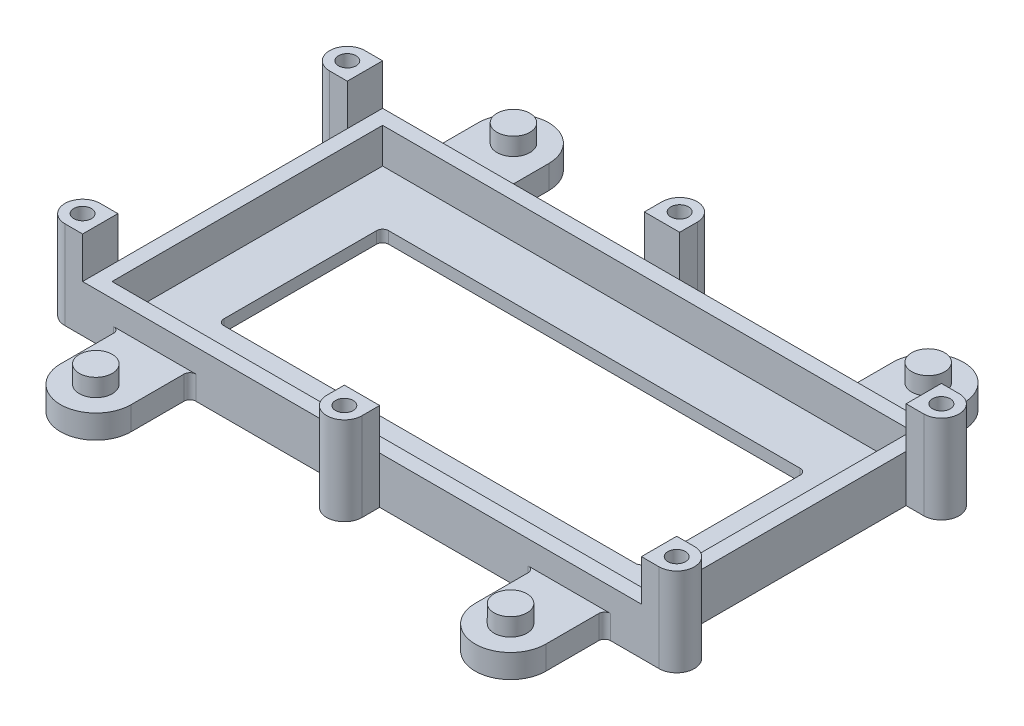
SolidWorks part; units mm, degrees
ref_plane "Front Plane" through (0, 0, 0) normal (0, 0, 1) x (1, 0, 0)
ref_plane "Top Plane" through (0, 0, 0) normal (0, 1, 0) x (1, 0, 0)
ref_plane "Right Plane" through (0, 0, 0) normal (1, 0, 0) x (0, 0, -1)
sketch "Sketch1" plane through (0, 0, 0) normal (0, 1, 0) x (1, 0, 0)
  line L1 (-55.9294, 26.1636) -> (39.0706, 26.1636)
  line L2 (-55.9294, 26.1636) -> (-55.9294, -24.8364)
  line L3 (-55.9294, -24.8364) -> (39.0706, -24.8364)
  line L4 (39.0706, 26.1636) -> (39.0706, -24.8364)
  dimension "D1" = 51
  dimension "D2" = 95
extrude "Boss-Extrude1" add sketch "Sketch1" along normal blind 2
sketch "Sketch2" plane through (0, 2, 0) normal (0, 1, 0) x (1, 0, 0)
  line L1 (-55.9294, 26.1636) -> (39.0706, 26.1636)
  line L2 (-55.9294, 26.1636) -> (-55.9294, -24.8364)
  line L3 (-55.9294, -24.8364) -> (39.0706, -24.8364)
  line L4 (39.0706, 26.1636) -> (39.0706, -24.8364)
  line L5 (36.5706, 23.6636) -> (-53.4294, 23.6636)
  line L6 (36.5706, 23.6636) -> (36.5706, -22.3364)
  line L7 (36.5706, -22.3364) -> (-53.4294, -22.3364)
  line L8 (-53.4294, 23.6636) -> (-53.4294, -22.3364)
  dimension "D1" = 2.5
  dimension "D2" = 2.5
  dimension "D3" = 2.5
  dimension "D4" = 2.5
extrude "Boss-Extrude2" add sketch "Sketch2" along normal blind 6
sketch "Sketch3" plane through (0, 2, 0) normal (0, 1, 0) x (1, 0, 0)
  line L0 (36.5706, -22.3364) -> (36.5706, 23.6636) construction
  line L1 (-44.4294, -13.3364) -> (27.5706, -13.3364)
  line L2 (-44.4294, -13.3364) -> (-44.4294, 14.6636)
  line L3 (-44.4294, 14.6636) -> (27.5706, 14.6636)
  line L4 (27.5706, -13.3364) -> (27.5706, 14.6636)
  line L5 (36.5706, 23.6636) -> (-53.4294, 23.6636) construction
  line L6 (-53.4294, -22.3364) -> (36.5706, -22.3364) construction
  line L7 (-53.4294, 23.6636) -> (-53.4294, -22.3364) construction
  dimension "D1" = 9
  dimension "D2" = 9
  dimension "D3" = 9
  dimension "D4" = 9
extrude "Cut-Extrude1" cut sketch "Sketch3" against normal through all
sketch "Sketch5" plane through (0, 0, 0) normal (0, -1, 0) x (1, 0, 0)
  line L0 (39.0706, -26.1636) -> (-55.9294, -26.1636) construction
  line L1 (-49.6794, -26.1636) -> (-37.6794, -26.1636)
  line L2 (-49.6794, -26.1636) -> (-49.6794, -36.1636)
  line L4 (-37.6794, -26.1636) -> (-37.6794, -36.1636)
  line L5 (-55.9294, -26.1636) -> (-55.9294, 24.8364) construction
  line L6 (-55.9294, -0.6636) -> (39.0706, -0.6636) construction
  line L7 (39.0706, 24.8364) -> (39.0706, -26.1636) construction
  line L8 (-8.4294, -26.1636) -> (-8.4294, 24.8364) construction
  line L9 (-55.9294, 24.8364) -> (39.0706, 24.8364) construction
  line L10 (-49.6794, 24.8364) -> (-49.6794, 34.8364)
  line L11 (-49.6794, 24.8364) -> (-37.6794, 24.8364)
  line L12 (-37.6794, 24.8364) -> (-37.6794, 34.8364)
  line L13 (32.8206, -26.1636) -> (32.8206, -36.1636)
  line L14 (32.8206, -26.1636) -> (20.8206, -26.1636)
  line L15 (20.8206, -26.1636) -> (20.8206, -36.1636)
  line L16 (32.8206, 24.8364) -> (20.8206, 24.8364)
  line L17 (20.8206, 24.8364) -> (20.8206, 34.8364)
  line L18 (32.8206, 24.8364) -> (32.8206, 34.8364)
  arc A0 (-49.6794, -36.1636) -> (-37.6794, -36.1636) centre (-43.6794, -36.1636) ccw
  arc A1 (-49.6794, 34.8364) -> (-37.6794, 34.8364) centre (-43.6794, 34.8364) cw
  arc A2 (32.8206, -36.1636) -> (20.8206, -36.1636) centre (26.8206, -36.1636) cw
  arc A3 (32.8206, 34.8364) -> (20.8206, 34.8364) centre (26.8206, 34.8364) ccw
  dimension "D1" = 6.25
  dimension "D2" = 12
  dimension "D3" = 10
extrude "Boss-Extrude3" add sketch "Sketch5" against normal blind 4
sketch "Sketch6" plane through (0, 4, 0) normal (0, 1, 0) x (1, 0, 0)
  circle A0 centre (-43.6794, 36.1636) radius 2.8
  circle A1 centre (26.8206, 36.1636) radius 2.8
  circle A2 centre (26.8206, -34.8364) radius 2.8
  circle A3 centre (-43.6794, -34.8364) radius 2.8
  dimension "D1" = 5.6
  dimension "D2" = 5.6
  dimension "D3" = 5.6
  dimension "D4" = 5.6
extrude "Boss-Extrude4" add sketch "Sketch6" along normal blind 3
sketch "Sketch8" plane through (0, 0, 0) normal (0, -1, 0) x (1, 0, 0)
  line L1 (-55.9294, 24.8364) -> (-58.9294, 24.8364)
  line L2 (-55.9294, 24.8364) -> (-55.9294, 18.8364)
  line L3 (-55.9294, 18.8364) -> (-58.9294, 18.8364)
  line L5 (-5.4294, -26.1636) -> (-5.4294, -29.1636)
  line L9 (-55.9294, -20.1636) -> (-58.9294, -20.1636)
  line L10 (-55.9294, -26.1636) -> (-55.9294, -20.1636)
  line L11 (-55.9294, -26.1636) -> (-58.9294, -26.1636)
  line L12 (-37.6794, 24.8364) -> (20.8206, 24.8364) construction
  line L14 (39.0706, -26.1636) -> (42.0706, -26.1636)
  line L15 (39.0706, -26.1636) -> (39.0706, -20.1636)
  line L16 (39.0706, -20.1636) -> (42.0706, -20.1636)
  line L17 (39.0706, 18.8364) -> (42.0706, 18.8364)
  line L18 (39.0706, 24.8364) -> (39.0706, 18.8364)
  line L19 (39.0706, 24.8364) -> (42.0706, 24.8364)
  line L20 (-11.4294, 24.8364) -> (-5.4294, 24.8364)
  line L21 (-11.4294, 24.8364) -> (-11.4294, 27.8364)
  line L23 (-5.4294, 24.8364) -> (-5.4294, 27.8364)
  line L24 (-11.4294, -26.1636) -> (-11.4294, -29.1636)
  line L25 (-11.4294, -26.1636) -> (-5.4294, -26.1636)
  arc A0 (-58.9294, 24.8364) -> (-58.9294, 18.8364) centre (-58.9294, 21.8364) ccw
  circle A1 centre (-58.9294, 21.8364) radius 1.5
  circle A2 centre (-58.9294, -23.1636) radius 1.5
  arc A3 (-58.9294, -26.1636) -> (-58.9294, -20.1636) centre (-58.9294, -23.1636) cw
  arc A4 (42.0706, -26.1636) -> (42.0706, -20.1636) centre (42.0706, -23.1636) ccw
  circle A5 centre (42.0706, -23.1636) radius 1.5
  circle A6 centre (42.0706, 21.8364) radius 1.5
  arc A7 (42.0706, 24.8364) -> (42.0706, 18.8364) centre (42.0706, 21.8364) cw
  arc A8 (-5.4294, 27.8364) -> (-11.4294, 27.8364) centre (-8.4294, 27.8364) ccw
  circle A9 centre (-8.4294, 27.8364) radius 1.5
  circle A10 centre (-8.4294, -29.1636) radius 1.5
  arc A11 (-5.4294, -29.1636) -> (-11.4294, -29.1636) centre (-8.4294, -29.1636) cw
  dimension "D3" = 6
  dimension "D1" = 3
  dimension "D2" = 6
  dimension "D5" = 3
extrude "Boss-Extrude6" add sketch "Sketch8" against normal blind 15
fillet "Fillet1" radius 1 12 edges at (32.8206, 2, -26.1636) (20.8206, 2, -26.1636) (-37.6794, 2, -26.1636) (-49.6794, 2, -26.1636) (-49.6794, 2, 24.8364) (-37.6794, 2, 24.8364) (32.8206, 2, 24.8364) (20.8206, 2, 24.8364) (27.5706, 1, 13.3364) (27.5706, 1, -14.6636) (-44.4294, 1, 13.3364) (-44.4294, 1, -14.6636)
